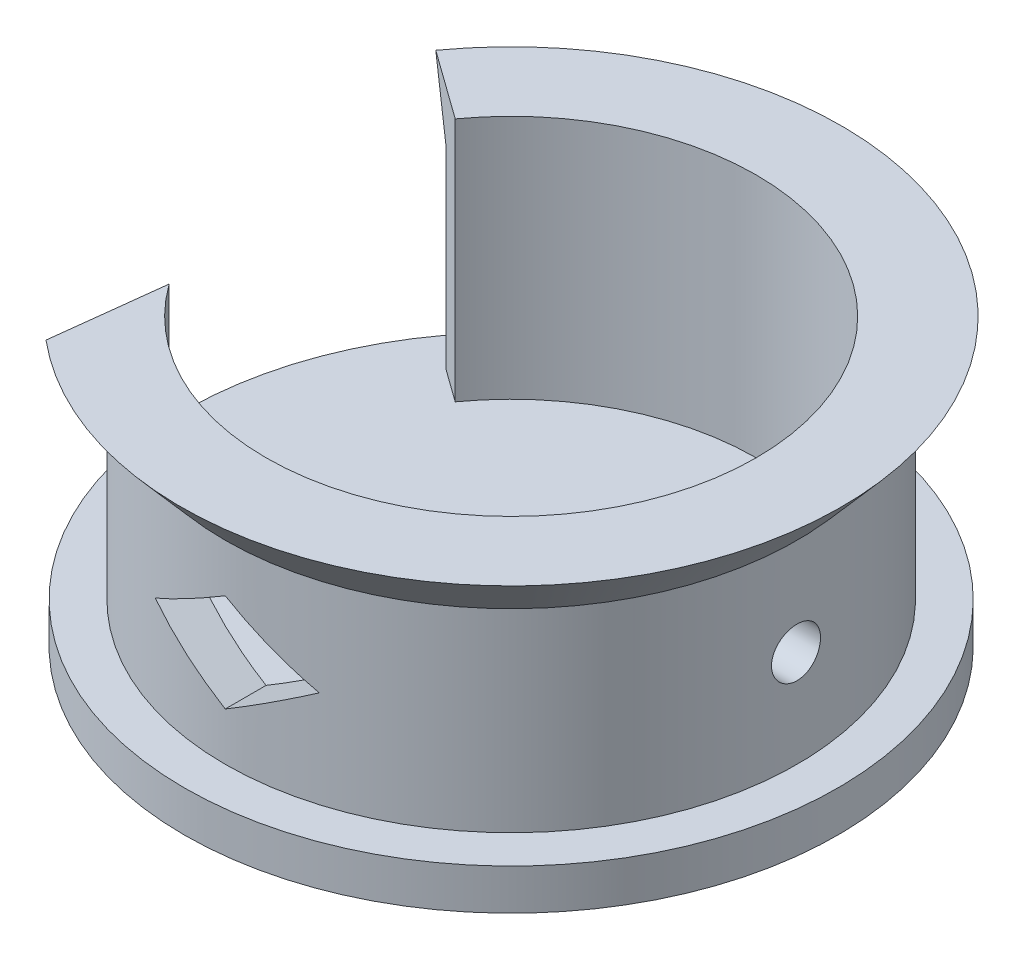
SolidWorks part; units mm, degrees
ref_plane "Front Plane" through (0, 0, 0) normal (0, 0, 1) x (1, 0, 0)
ref_plane "Top Plane" through (0, 0, 0) normal (0, 1, 0) x (1, 0, 0)
ref_plane "Right Plane" through (0, 0, 0) normal (1, 0, 0) x (0, 0, -1)
sketch "Sketch4" plane through (0, 0, 0) normal (0, 1, 0) x (1, 0, 0)
  circle A0 centre (0, 0) radius 8
extrude "Boss-Extrude3" add sketch "Sketch4" along normal blind 1
sketch "Sketch5" plane through (0, 1, 0) normal (0, 1, 0) x (1, 0, 0)
  circle A0 centre (0, 0) radius 7
  circle A1 centre (0, 0) radius 6
extrude "Boss-Extrude4" add sketch "Sketch5" along normal blind 4.75
sketch "Sketch6" plane through (0, 0, 0) normal (0, 0, 1) x (1, 0, 0)
  line L0 (0, 5.75) -> (7, 5.75)
  line L1 (6, 5.75) -> (-6, 5.75) construction
  line L7 (6, 7) -> (7, 5.75)
  line L8 (0, 7) -> (6, 7)
  line L10 (0, 5.75) -> (0, 7)
revolve "Revolve4" add sketch "Sketch6" angle 360 about L10
sketch "Sketch9" plane through (0, 7, 0) normal (0, 1, 0) x (1, 0, 0)
  circle A0 centre (0, 0) radius 6
extrude "Cut-Extrude3" cut sketch "Sketch9" against normal blind 3
sketch "Sketch11" plane through (0, 0, 0) normal (0, 0, 1) x (1, 0, 0)
  line L0 (0, 3.375) -> (0, 4.575)
  line L1 (0, 3.375) -> (0, 2.175)
  line L2 (0, 3.375) -> (-1.2, 3.375)
  line L3 (0, 3.375) -> (1.2, 3.375)
  line L5 (0, 2.175) -> (2.0078, 3.3732)
  line L6 (0, 4.575) -> (2.0078, 3.3732)
  line L7 (0, 3.375) -> (-2.0095, 3.375)
  line L8 (-2.0095, 3.375) -> (0, 4.575)
  line L9 (-2.0095, 3.375) -> (0, 2.175)
  line L10 (2.0078, 3.3732) -> (2, 3.3732)
  line L11 (-2.0095, 3.375) -> (-2, 3.375)
  line L15 (0, 3.375) -> (2.0078, 3.3732)
  point P10 (-2.0095, 3.375)
  point P11 (2.0078, 3.3732)
extrude "Cut-Extrude7" cut sketch "Sketch11" along normal blind 10 contours L3 L15 L6 L0 | L8 L7 L2 L0 | L7 L9 L1 L2 | L15 L3 L1 L5
sketch "Sketch13" plane through (0, 1, 0) normal (0, 1, 0) x (1, 0, 0)
  circle A0 centre (0, 0) radius 2.4
extrude "Cut-Extrude8" cut sketch "Sketch13" against normal blind 10
sketch "Sketch14" plane through (0, 0, 0) normal (0, 0, 1) x (1, 0, 0)
  line L0 (6, 7) -> (6, 5.75)
  line L1 (7, 5.75) -> (-7, 5.75) construction
  line L2 (6, 5.75) -> (7, 5.75)
  line L3 (6, 7) -> (8.0847, 7)
  line L4 (0, 5.75) -> (0, 7)
  line L5 (7, 5.75) -> (8.0847, 7)
  line L6 (6, 7) -> (-6, 7) construction
  line L7 (7, 5.75) -> (8.0847, 7)
revolve "Revolve5" add sketch "Sketch14" angle 360 about L4
sketch "Sketch15" plane through (0, 7, 0) normal (0, 1, 0) x (1, 0, 0)
  line L0 (-4.8719, -3.5021) -> (-5.1915, -6.1977)
  line L1 (-5.1915, -6.1977) -> (-9.543, -4.8499)
  line L2 (-4.8719, 3.5021) -> (-6.5646, 4.719)
  circle A0 centre (0, 0) radius 6 construction
  circle A1 centre (0, 0) radius 8.0847 construction
  circle A2 centre (0, 0) radius 6
  circle A3 centre (0, 0) radius 8.0847
  circle M2 centre (0, 0) radius 8.0847
  circle M3 centre (0, 0) radius 6
extrude "Cut-Extrude9" cut sketch "Sketch15" against normal blind 6 contours L2 L0 M3 M2
sketch "Sketch16" plane through (0, 0, 0) normal (1, 0, 0) x (0, 0, -1)
  line L0 (0, 5.75) -> (0, 1)
  line L1 (-7, 5.75) -> (7, 5.75) construction
  line L2 (8, 1) -> (-8, 1) construction
  circle A0 centre (0, 3.375) radius 0.6
extrude "Cut-Extrude10" cut sketch "Sketch16" along normal blind 10 contours L0 A0 | L0 A0
